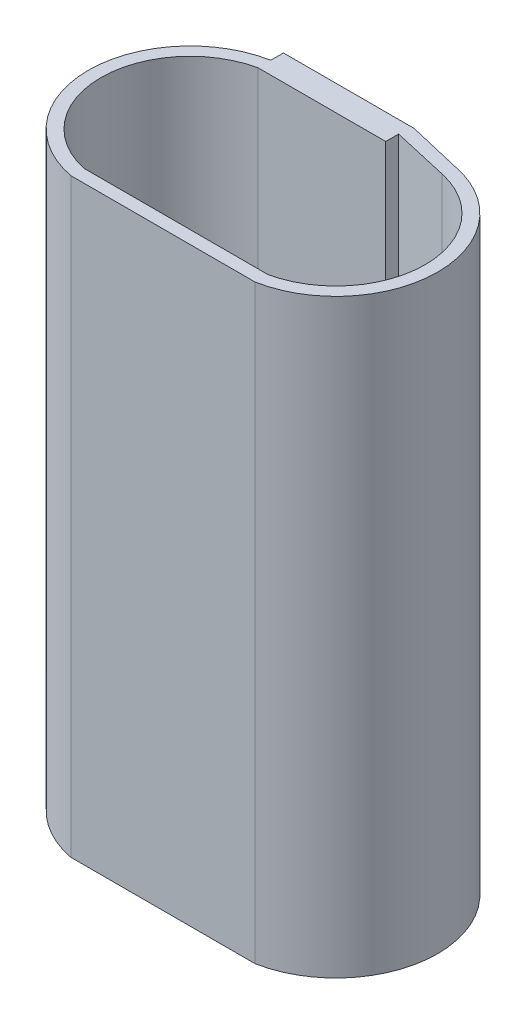
SolidWorks part; units mm, degrees
material "Copper"
ref_plane "Front Plane" through (0, 0, 0) normal (0, 0, 1) x (1, 0, 0)
ref_plane "Top Plane" through (0, 0, 0) normal (0, 1, 0) x (1, 0, 0)
ref_plane "Right Plane" through (0, 0, 0) normal (1, 0, 0) x (0, 0, -1)
sketch "Sketch1" plane through (0, 0, 0) normal (0, 1, 0) x (1, 0, 0)
  line L5 (-10.4634, 10.3895) -> (4.7888, 10.3895)
  line L7 (11.5366, -10.3895) -> (-10.4634, -10.3895)
  line L9 (-10.4634, -11.9295) -> (11.5366, -11.9295)
  line L10 (11.5366, 10.3895) -> (4.7888, 11.9295)
  line L12 (5.1329, 13.4376) -> (11.5366, 11.9295)
  line L13 (4.7888, 10.3895) -> (4.7888, 11.9295)
  line L14 (-10.4634, 11.9295) -> (4.7888, 11.9295)
  line L15 (4.7888, 11.9295) -> (-10.4634, 11.9295)
  line L16 (-10.4634, 13.4376) -> (5.1329, 13.4376)
  line L17 (-10.4634, 13.4376) -> (-10.4634, 11.9295)
  arc A2 (-10.4634, -10.3895) -> (-10.4634, 10.3895) centre (-8.1684, 0) cw
  arc A3 (11.5366, -10.3895) -> (11.5366, 10.3895) centre (9.2416, 0) ccw
  arc A4 (-10.4634, 11.9295) -> (-10.4573, -11.9307) centre (-8.1684, 0) ccw
  arc A5 (11.5366, -11.9295) -> (11.5306, 11.9307) centre (9.2416, 0) ccw
  dimension "D2" = 1.54
extrude "Boss-Extrude1" add sketch "Sketch1" along normal blind 70.45
sketch "Sketch2" plane through (-10.4634, 0, 0) normal (-1, 0, 0) x (0, 0, 1)
  circle A0 centre (-12.6819, 34.0139) radius 0.5747
  circle A1 centre (-12.6819, 36.4422) radius 0.5727
extrude "Boss-Extrude2" add sketch "Sketch2" along normal blind 2
